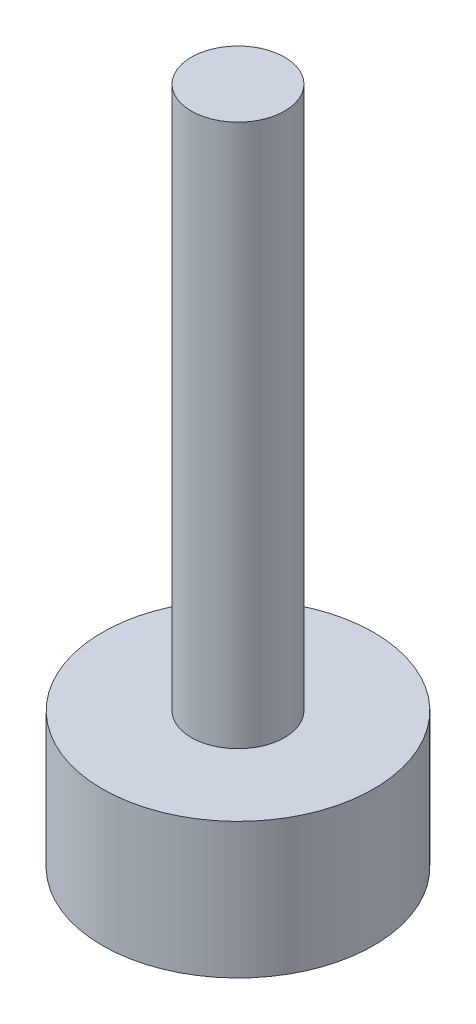
SolidWorks part; units mm, degrees
ref_plane "Front Plane" through (0, 0, 0) normal (0, 0, 1) x (1, 0, 0)
ref_plane "Top Plane" through (0, 0, 0) normal (0, 1, 0) x (1, 0, 0)
ref_plane "Right Plane" through (0, 0, 0) normal (1, 0, 0) x (0, 0, -1)
sketch "Sketch1" plane through (0, 0, 0) normal (0, 1, 0) x (1, 0, 0)
  circle A0 centre (0, 0) radius 1.0922
  dimension "D1" = 2.1844
sketch "Sketch2" plane through (0, 0, 0) normal (0, 1, 0) x (1, 0, 0)
  circle A0 centre (0, 0) radius 3.175
  dimension "D1" = 6.35
extrude "Boss-Extrude2" add sketch "Sketch2" against normal blind 3.175
extrude "Boss-Extrude3" add sketch "Sketch1" along normal blind 12.7
